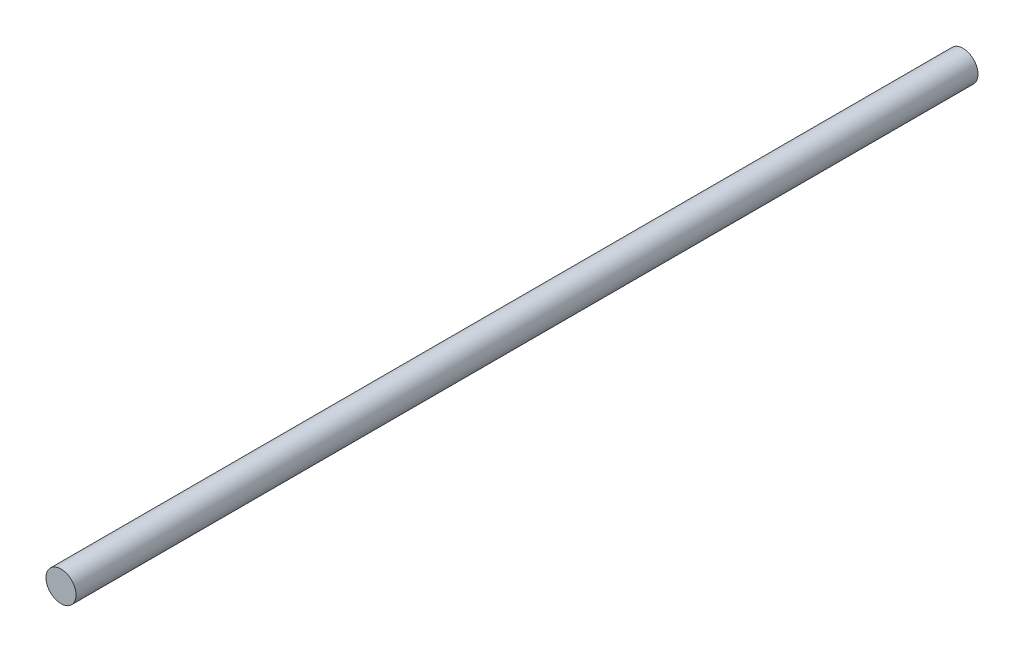
SolidWorks part; units mm, degrees
ref_plane "Front Plane" through (0, 0, 0) normal (0, 0, 1) x (1, 0, 0)
ref_plane "Top Plane" through (0, 0, 0) normal (0, 1, 0) x (1, 0, 0)
ref_plane "Right Plane" through (0, 0, 0) normal (1, 0, 0) x (0, 0, -1)
sketch "Sketch1" plane through (0, 0, 0) normal (0, 0, 1) x (1, 0, 0)
  circle A0 centre (0, 0) radius 10
  dimension "D1" = 20
extrude "Boss-Extrude1" add sketch "Sketch1" along normal blind 600
